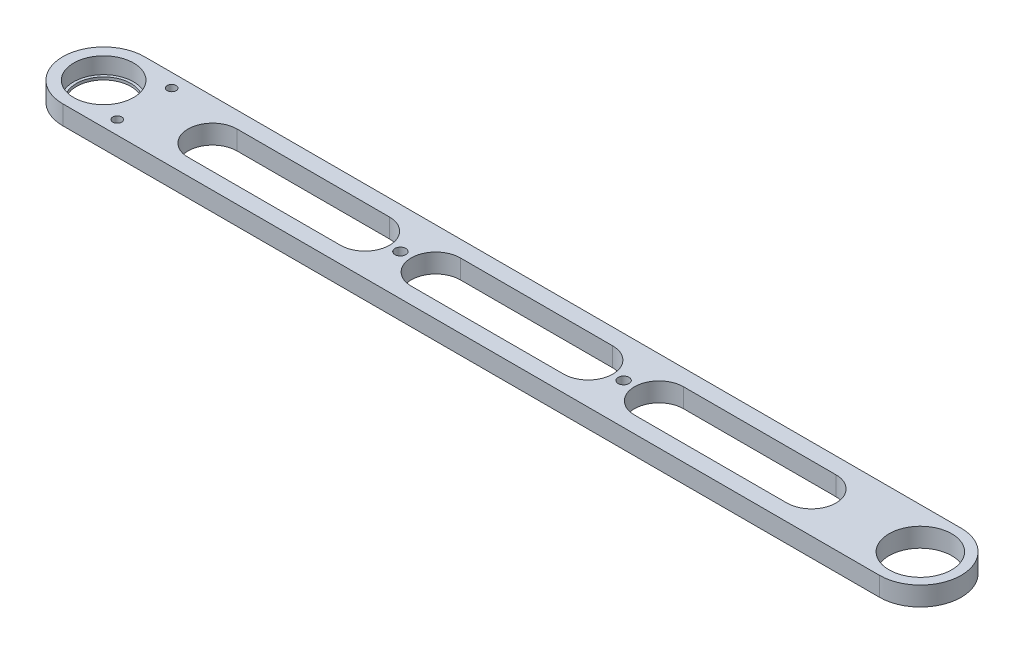
SolidWorks part; units mm, degrees
material "1060 Alloy"
ref_plane "Front Plane" through (0, 0, 0) normal (0, 0, 1) x (1, 0, 0)
ref_plane "Top Plane" through (0, 0, 0) normal (0, 1, 0) x (1, 0, 0)
ref_plane "Right Plane" through (0, 0, 0) normal (1, 0, 0) x (0, 0, -1)
sketch "Sketch1" plane through (0, 0, 0) normal (0, 1, 0) x (1, 0, 0)
  line L0 (-44.2539, 0) -> (44.2539, 0) construction
  line L1 (0, 21.7575) -> (0, -21.3381) construction
  line L2 (0, -44.7868) -> (0, 44.7868) construction
  line L3 (150, -15) -> (-150, -15)
  line L4 (-150, 15) -> (150, 15)
  line L5 (110, 9) -> (54, 9)
  line L6 (28, 9) -> (-28, 9)
  line L7 (-54, 9) -> (-110, 9)
  line L8 (-110, -9) -> (-54, -9)
  line L9 (-28, -9) -> (28, -9)
  line L10 (54, -9) -> (110, -9)
  line L11 (-45, 0) -> (-37, 0) construction
  line L12 (45, 0) -> (37, 0) construction
  arc A0 (-150, 15) -> (-150, -15) centre (-150, 0) ccw
  arc A1 (150, -15) -> (150, 15) centre (150, 0) ccw
  circle A2 centre (150, 0) radius 11.5
  circle A3 centre (-150, 0) radius 10
  arc A4 (-110, -9) -> (-110, 9) centre (-110, 0) cw
  arc A5 (-54, -9) -> (-54, 9) centre (-54, 0) ccw
  arc A6 (-28, -9) -> (-28, 9) centre (-28, 0) cw
  arc A7 (28, -9) -> (28, 9) centre (28, 0) ccw
  arc A8 (54, -9) -> (54, 9) centre (54, 0) cw
  arc A9 (110, -9) -> (110, 9) centre (110, 0) ccw
  circle A10 centre (41, 0) radius 2
  circle A11 centre (-41, 0) radius 2
  dimension "D2" = 15
  dimension "D3" = 6
  dimension "D6" = 26
  dimension "D8" = 4
  dimension "D1" = 150
  dimension "D4" = 40
  dimension "D5" = 26
  dimension "D7" = 40
extrude "Boss-Extrude1" add sketch "Sketch1" along normal blind 7
sketch "Sketch2" plane through (0, 7, 0) normal (0, 1, 0) x (1, 0, 0)
  circle A0 centre (-150, 0) radius 11
extrude "Cut-Extrude1" cut sketch "Sketch2" against normal blind 6
hole_wizard "M4 Tapped Hole1" positions "Sketch3" profile "Sketch4" tap size "M4" standard "ISO"
sketch "Sketch3" plane through (0, 7, 0) normal (0, 1, 0) x (1, 0, 0)
  line L0 (-150, -15) -> (150, -15) construction
  line L1 (-150, 0) -> (-109.2137, 0) construction
  point P0 (-135, 10)
  point P2 (-135, -10)
  dimension "D1" = 5
  dimension "D2" = 15
sketch "Sketch4" plane through (-135, 7, -10) normal (1, 0, 0) x (0, 0, 1)
  line L0 (0, 0) -> (0, 5.9914)
  line L1 (0, 5.9914) -> (1.65, 5)
  line L2 (1.65, 5) -> (1.65, 0)
  line L5 (1.65, 0) -> (0, 0)
  line L10 (0, 5.9914) -> (-1.65, 5) construction
  line L11 (0, -6.35) -> (0, 107.95) construction
  dimension "Tap Drill Dia." = 3.3
  dimension "Tap Drill Depth" = 5
  dimension "Drill Angle" = 118
cosmetic thread "Hole Thread1" parameters "D1"=5, "D2"=4
cosmetic thread "Hole Thread2" parameters "D1"=5, "D2"=4
ref_plane "Plane1" through (0, 3.5, 0) normal (0, -1, 0) x (-1, 0, 0)
